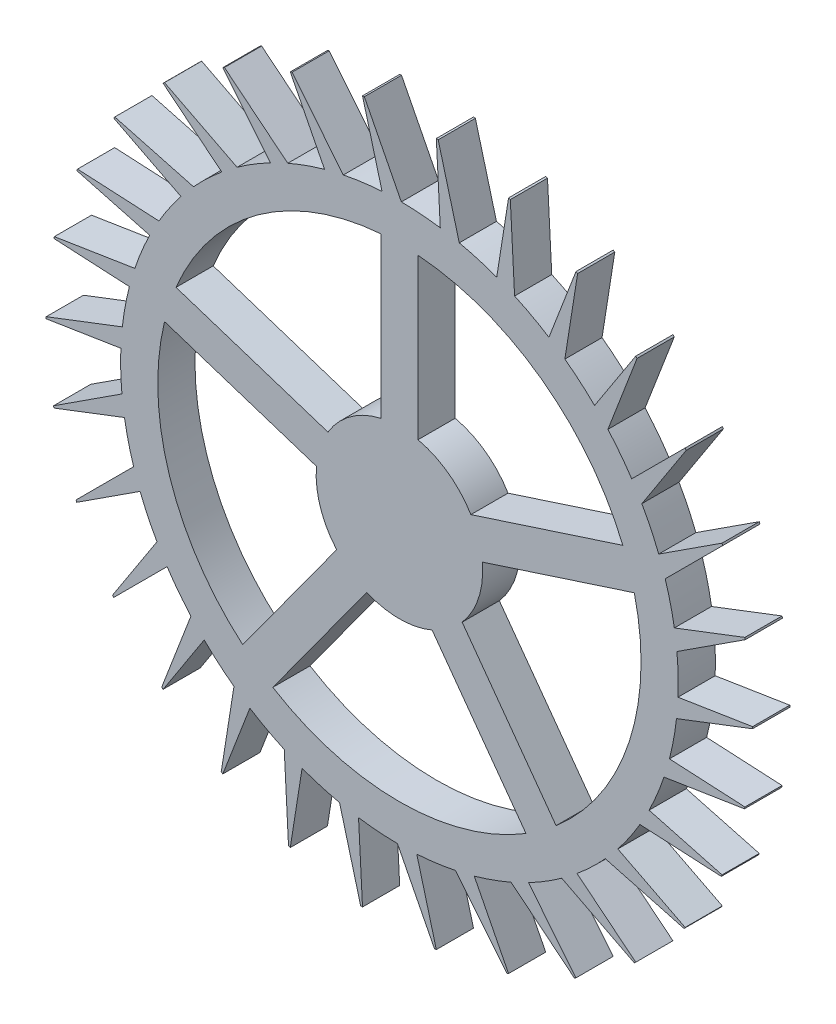
SolidWorks part; units mm, degrees
ref_plane "Front Plane" through (0, 0, 0) normal (0, 0, 1) x (1, 0, 0)
ref_plane "Top Plane" through (0, 0, 0) normal (0, 1, 0) x (1, 0, 0)
ref_plane "Right Plane" through (0, 0, 0) normal (1, 0, 0) x (0, 0, -1)
sketch "Sketch1" plane through (0, 0, 0) normal (0, 0, 1) x (1, 0, 0)
  line L0 (0, 0) -> (197.8334, 0) construction
  line L1 (0, 0) -> (65.5359, -13.9301) construction
  line L2 (74.9326, -3.1784) -> (95, 0)
  line L3 (94.9987, -0.5) -> (65.9814, -11.6387)
  line L4 (72.6343, -18.6883) -> (92.924, -19.7516)
  line L5 (92.8188, -20.2404) -> (62.1197, -25.1027)
  line L6 (67.1616, -33.3814) -> (86.7868, -38.64)
  line L7 (86.5822, -39.0962) -> (55.5431, -37.4695)
  line L8 (58.7536, -46.6156) -> (76.8566, -55.8396)
  line L9 (76.5617, -56.2433) -> (46.539, -48.1988)
  line L10 (47.7777, -57.8125) -> (63.5674, -70.5988)
  line L11 (63.195, -70.9323) -> (35.5009, -56.8215)
  line L12 (34.7138, -66.4827) -> (47.5, -82.2724)
  line L13 (47.0663, -82.5213) -> (22.9113, -62.9609)
  line L14 (20.1327, -72.2473) -> (29.3566, -90.3504)
  line L15 (28.8807, -90.5036) -> (9.3203, -66.3486)
  line L16 (4.6716, -74.8544) -> (9.9302, -94.4796)
  line L17 (9.4328, -94.5305) -> (-4.678, -66.8365)
  line L18 (-10.9935, -74.1899) -> (-9.9302, -94.4796)
  line L19 (-10.4273, -94.426) -> (-18.4719, -64.4033)
  line L20 (-26.1783, -70.283) -> (-29.3566, -90.3504)
  line L21 (-29.8317, -90.1946) -> (-31.4584, -59.1555)
  line L22 (-40.2189, -63.3044) -> (-47.5, -82.2724)
  line L23 (-47.9324, -82.0213) -> (-43.0701, -51.3222)
  line L24 (-52.5017, -53.5591) -> (-63.5674, -70.5988)
  line L25 (-63.9381, -70.2632) -> (-52.7994, -41.2459)
  line L26 (-62.49, -41.4729) -> (-76.8566, -55.8396)
  line L27 (-77.1494, -55.4343) -> (-60.2211, -29.367)
  line L28 (-69.7471, -27.5743) -> (-86.7868, -38.64)
  line L29 (-86.989, -38.1827) -> (-65.0109, -16.2046)
  line L30 (-73.956, -12.4705) -> (-92.924, -19.7516)
  line L31 (-93.0267, -19.2623) -> (-66.9593, -2.3339)
  line L32 (-74.9326, 3.1784) -> (-95, 0)
  line L33 (-94.9987, 0.5) -> (-65.9814, 11.6387)
  line L34 (-72.6343, 18.6883) -> (-92.924, 19.7516)
  line L35 (-92.8188, 20.2404) -> (-62.1197, 25.1027)
  line L36 (-67.1616, 33.3814) -> (-86.7868, 38.64)
  line L37 (-86.5822, 39.0962) -> (-55.5431, 37.4695)
  line L38 (-58.7536, 46.6156) -> (-76.8566, 55.8396)
  line L39 (-76.5617, 56.2433) -> (-46.539, 48.1988)
  line L40 (-47.7777, 57.8125) -> (-63.5674, 70.5988)
  line L41 (-63.195, 70.9323) -> (-35.5009, 56.8215)
  line L42 (0, 0) -> (65.9814, -11.6387) construction
  line L43 (-34.7138, 66.4827) -> (-47.5, 82.2724)
  line L44 (-47.0663, 82.5213) -> (-22.9113, 62.9609)
  line L45 (-20.1327, 72.2473) -> (-29.3566, 90.3504)
  line L46 (-28.8807, 90.5036) -> (-9.3203, 66.3486)
  line L47 (-4.6716, 74.8544) -> (-9.9302, 94.4796)
  line L48 (-9.4328, 94.5305) -> (4.678, 66.8365)
  line L49 (10.9935, 74.1899) -> (9.9302, 94.4796)
  line L50 (10.4273, 94.426) -> (18.4719, 64.4033)
  line L51 (26.1783, 70.283) -> (29.3566, 90.3504)
  line L52 (29.8317, 90.1946) -> (31.4584, 59.1555)
  line L53 (40.2189, 63.3044) -> (47.5, 82.2724)
  line L54 (47.9324, 82.0213) -> (43.0701, 51.3222)
  line L55 (52.5017, 53.5591) -> (63.5674, 70.5988)
  line L56 (63.9381, 70.2632) -> (52.7994, 41.2459)
  line L57 (62.49, 41.4729) -> (76.8566, 55.8396)
  line L58 (77.1494, 55.4343) -> (60.2211, 29.367)
  line L59 (69.7471, 27.5743) -> (86.7868, 38.64)
  line L60 (86.989, 38.1827) -> (65.0109, 16.2046)
  line L61 (73.956, 12.4705) -> (92.924, 19.7516)
  line L62 (0, 0) -> (0, 65) construction
  line L63 (-5, 64.8074) -> (-5, 21.8348)
  line L64 (5, 64.8074) -> (5, 21.8348)
  line L65 (63.1806, 15.2713) -> (22.3112, 1.9921)
  line L66 (60.0904, 24.7819) -> (19.2211, 11.5026)
  line L67 (34.0478, -55.3692) -> (8.7891, -20.6037)
  line L68 (42.1379, -49.4914) -> (16.8793, -14.7258)
  line L69 (-42.1379, -49.4914) -> (-16.8793, -14.7258)
  line L70 (-34.0478, -55.3692) -> (-8.7891, -20.6037)
  line L71 (-60.0904, 24.7819) -> (-19.2211, 11.5026)
  line L72 (-63.1806, 15.2713) -> (-22.3112, 1.9921)
  line L73 (93.0267, 19.2623) -> (66.9593, 2.3339)
  circle A0 centre (0, 0) radius 75
  arc A1 (92.924, -19.7516) -> (92.8188, -20.2404) centre (0, 0) cw
  arc A2 (86.7868, -38.64) -> (86.5822, -39.0962) centre (0, 0) cw
  arc A3 (76.8566, -55.8396) -> (76.5617, -56.2433) centre (0, 0) cw
  arc A4 (63.5674, -70.5988) -> (63.195, -70.9323) centre (0, 0) cw
  arc A5 (47.5, -82.2724) -> (47.0663, -82.5213) centre (0, 0) cw
  arc A6 (29.3566, -90.3504) -> (28.8807, -90.5036) centre (0, 0) cw
  arc A7 (9.9302, -94.4796) -> (9.4328, -94.5305) centre (0, 0) cw
  arc A8 (-9.9302, -94.4796) -> (-10.4273, -94.426) centre (0, 0) cw
  arc A9 (-29.3566, -90.3504) -> (-29.8317, -90.1946) centre (0, 0) cw
  arc A10 (-47.5, -82.2724) -> (-47.9324, -82.0213) centre (0, 0) cw
  arc A11 (-63.5674, -70.5988) -> (-63.9381, -70.2632) centre (0, 0) cw
  arc A12 (-76.8566, -55.8396) -> (-77.1494, -55.4343) centre (0, 0) cw
  arc A13 (-86.7868, -38.64) -> (-86.989, -38.1827) centre (0, 0) cw
  arc A14 (-92.924, -19.7516) -> (-93.0267, -19.2623) centre (0, 0) cw
  arc A15 (-95, 0) -> (-94.9987, 0.5) centre (0, 0) cw
  arc A16 (-92.924, 19.7516) -> (-92.8188, 20.2404) centre (0, 0) cw
  arc A17 (-86.7868, 38.64) -> (-86.5822, 39.0962) centre (0, 0) cw
  arc A18 (-76.8566, 55.8396) -> (-76.5617, 56.2433) centre (0, 0) cw
  arc A19 (-63.5674, 70.5988) -> (-63.195, 70.9323) centre (0, 0) cw
  arc A20 (-47.5, 82.2724) -> (-47.0663, 82.5213) centre (0, 0) cw
  arc A21 (-29.3566, 90.3504) -> (-28.8807, 90.5036) centre (0, 0) cw
  arc A22 (-9.9302, 94.4796) -> (-9.4328, 94.5305) centre (0, 0) cw
  arc A23 (9.9302, 94.4796) -> (10.4273, 94.426) centre (0, 0) cw
  arc A24 (29.3566, 90.3504) -> (29.8317, 90.1946) centre (0, 0) cw
  arc A25 (47.5, 82.2724) -> (47.9324, 82.0213) centre (0, 0) cw
  arc A26 (63.5674, 70.5988) -> (63.9381, 70.2632) centre (0, 0) cw
  arc A27 (76.8566, 55.8396) -> (77.1494, 55.4343) centre (0, 0) cw
  arc A28 (86.7868, 38.64) -> (86.989, 38.1827) centre (0, 0) cw
  arc A29 (92.924, 19.7516) -> (93.0267, 19.2623) centre (0, 0) cw
  circle A61 centre (0, 0) radius 65
  circle A62 centre (0, 0) radius 22.4
  circle A64 centre (0, 0) radius 95 construction
  arc A65 (95, 0) -> (94.9987, -0.5) centre (0, 0) cw
  point P158 (0, 0)
  point P181 (0, 0)
  dimension "D4" = 190
  dimension "D8" = 44.8
  dimension "D12" = 21
  dimension "D13" = 30
  dimension "D2" = 10
  dimension "D10" = 20
  dimension "D3" = 0.5
  dimension "D5" = 10
  dimension "D6" = 5
  dimension "D11" = 9
  dimension "D14" = 67
  dimension "D7" = 5
extrude "Boss-Extrude1" add sketch "Sketch1" along normal blind 10
